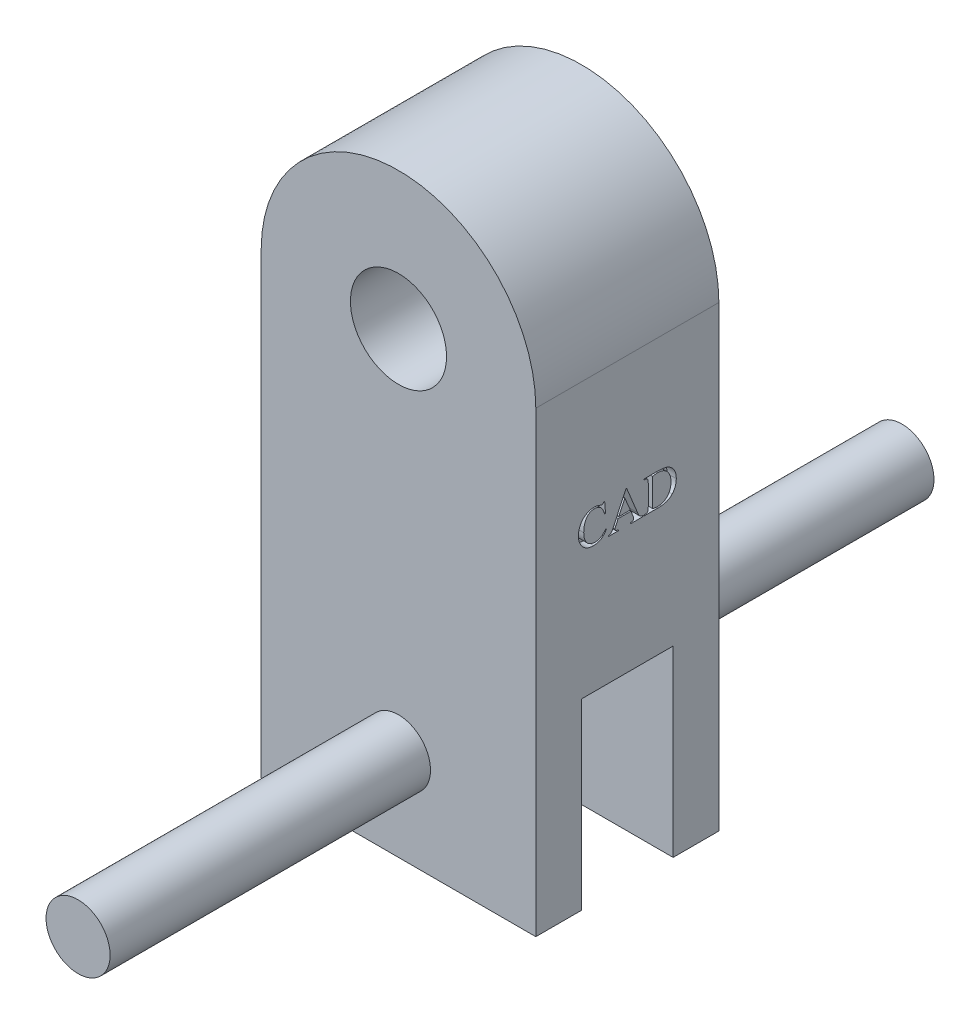
SolidWorks part; units mm, degrees
ref_plane "Front Plane" through (0, 0, 0) normal (0, 0, 1) x (1, 0, 0)
ref_plane "Top Plane" through (0, 0, 0) normal (0, 1, 0) x (1, 0, 0)
ref_plane "Right Plane" through (0, 0, 0) normal (1, 0, 0) x (0, 0, -1)
sketch "Sketch1" plane through (0, 0, 0) normal (0, 0, 1) x (1, 0, 0)
  line L0 (-15, 0) -> (-15, -50)
  line L1 (-15, -50) -> (15, -50)
  line L2 (15, -50) -> (15, 0)
  arc A0 (15, 0) -> (-15, 0) centre (0, 0) ccw
  circle A1 centre (0, 0) radius 5.25
  dimension "D1" = 10.5
  dimension "D2" = 30
  dimension "D3" = 50
extrude "Boss-Extrude1" add sketch "Sketch1" along normal mid plane 20
sketch "Sketch5" plane through (0, 0, 0) normal (1, 0, 0) x (0, 0, -1)
  line L0 (-10, -50) -> (10, -50) construction
  line L1 (-5, -50) -> (5, -50)
  line L2 (-5, -50) -> (-5, -30)
  line L3 (-5, -30) -> (5, -30)
  line L4 (5, -50) -> (5, -30)
  line L5 (-5, -50) -> (5, -30) construction
  line L6 (-5, -30) -> (5, -50) construction
  line L7 (-10, -50) -> (-10, 0) construction
  line L8 (10, -50) -> (10, 0) construction
  point P4 (0, -40)
  dimension "D1" = 5
  dimension "D2" = 5
  dimension "D3" = 20
extrude "Cut-Extrude2" cut sketch "Sketch5" against normal through all both and the other way through all
sketch "Sketch2" plane through (0, 0, 0) normal (0, 0, 1) x (1, 0, 0)
  line L0 (0, -40) -> (0, 0) construction
  line L1 (-15, -50) -> (15, -50) construction
  circle A0 centre (0, -40) radius 3.5
  dimension "D1" = 7
  dimension "D2" = 10
extrude "Boss-Extrude2" add sketch "Sketch2" along normal mid plane 90
sketch "Sketch6" plane through (15, 0, 0) normal (1, 0, 0) x (0, 0, -1)
  line L0 (-10, -16.1081) -> (10, -16.1081) construction
  line L1 (-10, -50) -> (-10, 0) construction
  line L2 (10, -50) -> (10, 0) construction
  text T0 "CAD" font "Times New Roman" height 3.5
extrude "Cut-Extrude3" cut sketch "Sketch6" against normal blind 1
equation "\"D2@Sketch5\"=\"D1@Sketch5\""
